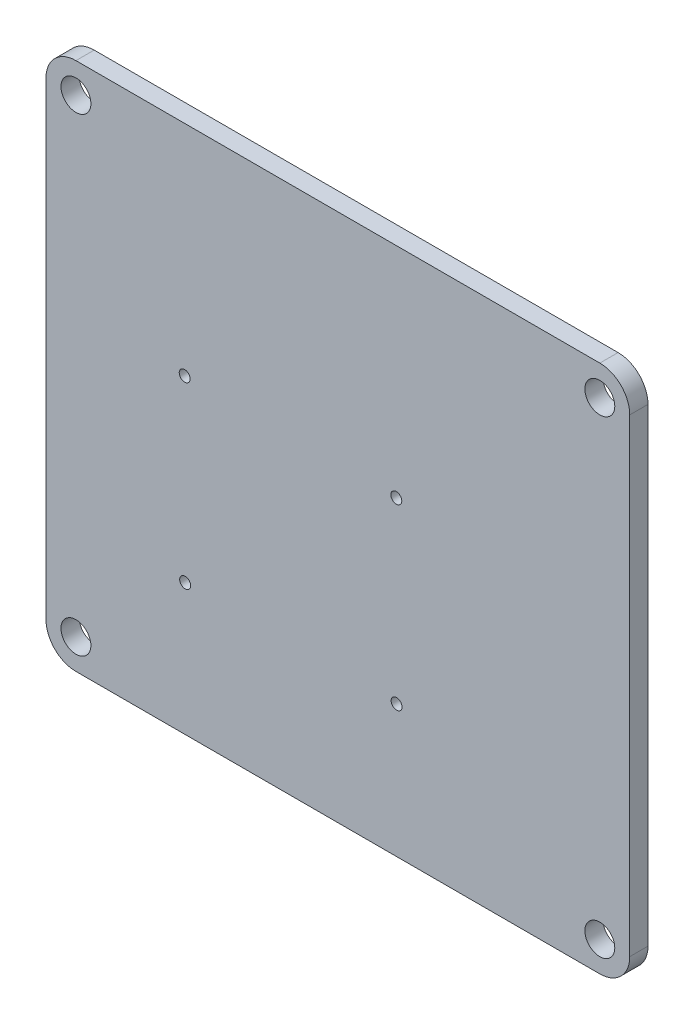
SolidWorks part; units mm, degrees
ref_plane "Alzado" through (0, 0, 0) normal (1, 0, 0) x (0, 1, 0)
ref_plane "Planta" through (0, 0, 0) normal (0, 0, 1) x (0, 1, 0)
ref_plane "Vista lateral" through (0, 0, 0) normal (0, 1, 0) x (-1, 0, 0)
sketch "Croquis1" plane through (0, 0, 0) normal (0, 0, 1) x (0, 1, 0)
  line L1 (-64.3, -80) -> (64.3, -80)
  line L2 (-72.5, -71.8) -> (-72.5, 71.8)
  line L3 (-64.3, 80) -> (64.3, 80)
  line L4 (72.5, -71.8) -> (72.5, 71.8)
  line L5 (-72.5, -80) -> (72.5, 80) construction
  line L6 (-72.5, 80) -> (72.5, -80) construction
  arc A0 (-64.3, -80) -> (-72.5, -71.8) centre (-64.3, -71.8) cw
  arc A1 (64.3, -80) -> (72.5, -71.8) centre (64.3, -71.8) ccw
  arc A2 (64.3, 80) -> (72.5, 71.8) centre (64.3, 71.8) cw
  arc A3 (-72.5, 71.8) -> (-64.3, 80) centre (-64.3, 71.8) cw
  circle A4 centre (-64.3, 71.8) radius 4.1
  circle A5 centre (64.3, 71.8) radius 4.1
  circle A6 centre (64.3, -71.8) radius 4.1
  circle A7 centre (-64.3, -71.8) radius 4.1
  point P0 (0, 0)
  dimension "D3" = 8.2
  dimension "D4" = 8.2
  dimension "D5" = 8.2
  dimension "D6" = 8.2
  dimension "D7" = 8.2
  dimension "D1" = 145
  dimension "D2" = 160
extrude "Saliente-Extruir1" add sketch "Croquis1" along normal blind 5 contours A3 L2 A0 L1 A1 L4 A2 L3 A7 A6 A5 A4
sketch "Croquis2" plane through (0, 0, 5) normal (0, 0, 1) x (0, -1, 0)
  circle A0 centre (-12.5732, -41.9866) radius 1.5
  circle A1 centre (-12.6185, 16.0134) radius 1.5
  circle A2 centre (36.2415, 16.0859) radius 1.5
  circle A3 centre (36.4267, -41.8638) radius 1.5
extrude "Cortar-Extruir1" cut sketch "Croquis2" against normal blind 10
